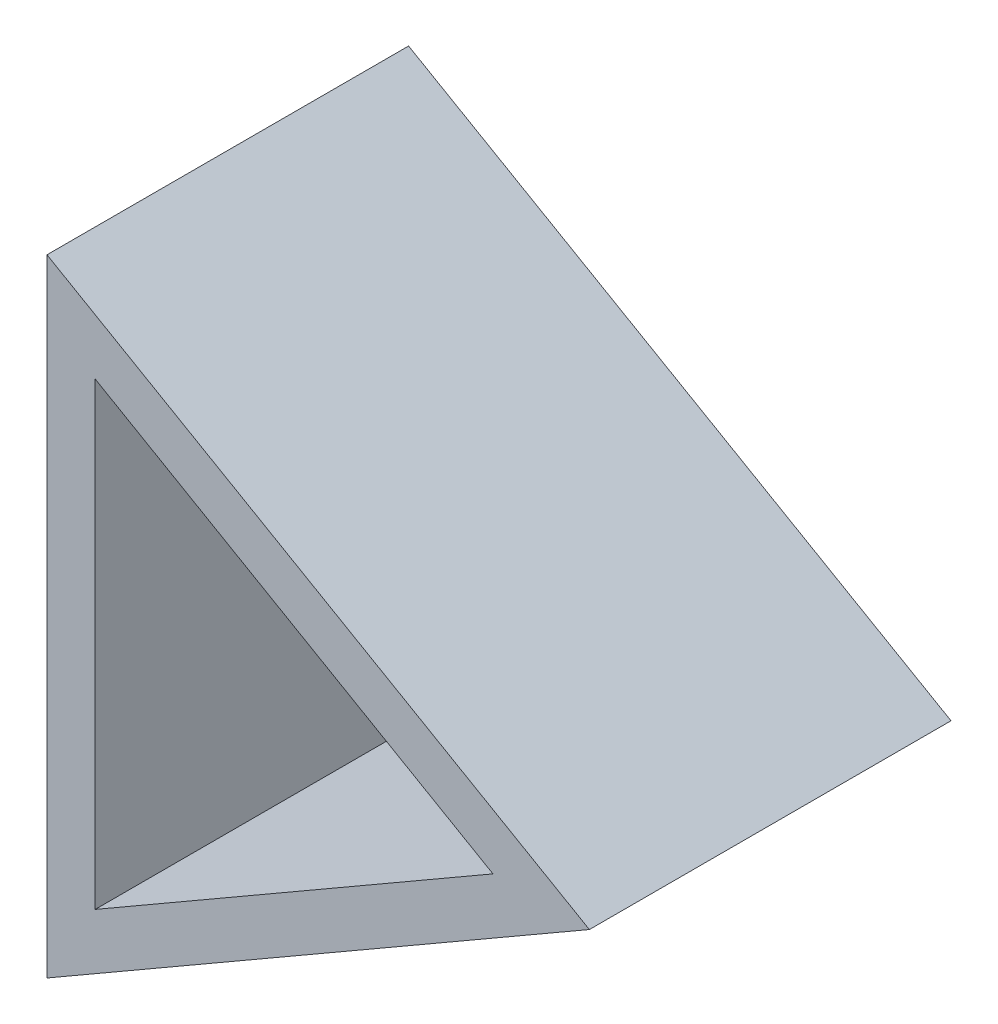
SolidWorks part; units mm, degrees
ref_plane "前视基准面" through (0, 0, 0) normal (0, 0, 1) x (1, 0, 0)
ref_plane "上视基准面" through (0, 0, 0) normal (0, 1, 0) x (1, 0, 0)
ref_plane "右视基准面" through (0, 0, 0) normal (1, 0, 0) x (0, 0, -1)
other "Configuration Table"
sketch "草图1" plane through (0, 0, 0) normal (0, 0, 1) x (1, 0, 0)
  line L1 (30, 0) -> (-15, 25.9808)
  line L2 (-15, 25.9808) -> (-15, -25.9808)
  line L3 (-15, -25.9808) -> (30, 0)
  circle A0 centre (0, 0) radius 15 construction
extrude "凸台-拉伸1" add sketch "草图1" along normal mid plane 30
shell "抽壳1" thickness 4
